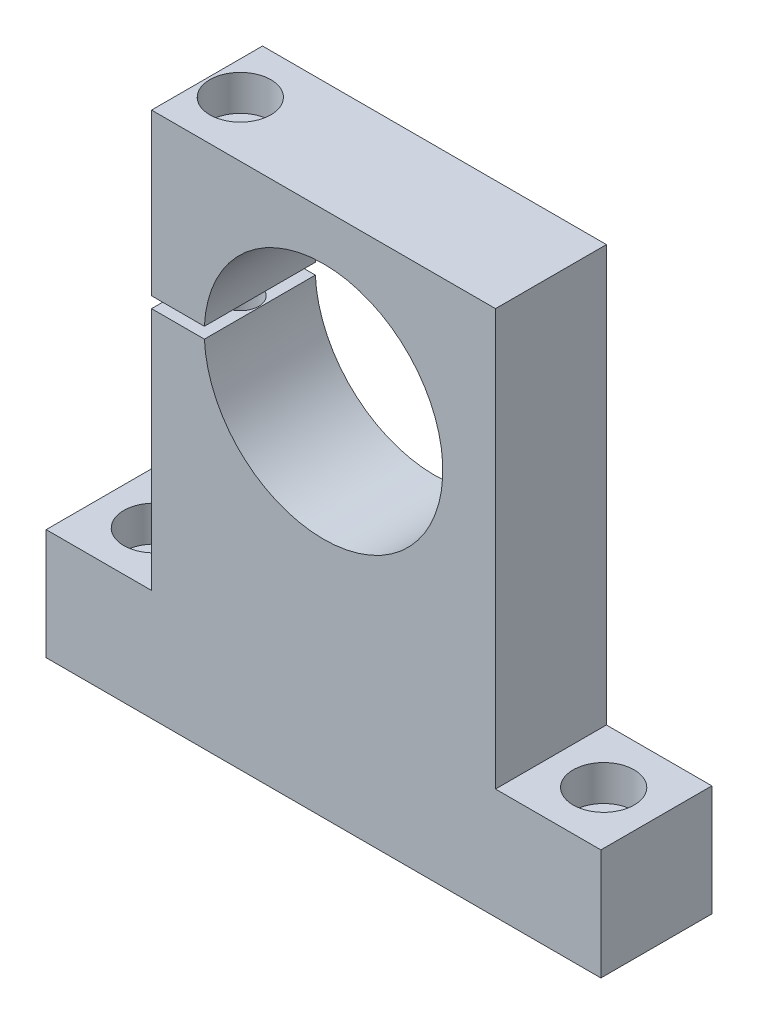
SolidWorks part; units mm, degrees
ref_plane "Piano frontale" through (0, 0, 0) normal (0, 0, 1) x (1, 0, 0)
ref_plane "Piano superiore" through (0, 0, 0) normal (0, 1, 0) x (1, 0, 0)
ref_plane "Piano destro" through (0, 0, 0) normal (1, 0, 0) x (0, 0, -1)
sketch "Schizzo1" plane through (0, 0, 0) normal (0, 0, 1) x (1, 0, 0)
  line L0 (0, 0) -> (100, 0)
  line L1 (0, 0) -> (0, 20)
  line L2 (0, 20) -> (19, 20)
  line L3 (19, 20) -> (19, 95)
  line L4 (19, 95) -> (81, 95)
  line L5 (50, 0) -> (50, 95) construction
  line L6 (100, 20) -> (81, 20)
  line L7 (100, 0) -> (100, 20)
  line L8 (81, 20) -> (81, 95)
  circle A0 centre (50, 65) radius 21.5
  dimension "D4" = 43
  dimension "D1" = 50
  dimension "D2" = 20
  dimension "D3" = 75
  dimension "D5" = 30
  dimension "D6" = 19
extrude "Estrusione-Estrusione1" add sketch "Schizzo1" along normal blind 20
sketch "Schizzo2" plane through (0, 20, 0) normal (0, 1, 0) x (1, 0, 0)
  line L0 (0, -10) -> (100, -10) construction
  line L1 (0, -20) -> (0, 0) construction
  line L2 (100, -20) -> (100, 0) construction
  line L3 (9.5, 0) -> (9.5, -20) construction
  line L4 (19, 0) -> (0, 0) construction
  line L5 (19, -20) -> (0, -20) construction
  line L6 (50, 0) -> (50, -20) construction
  line L7 (81, 0) -> (19, 0) construction
  line L8 (81, -20) -> (19, -20) construction
  point P12 (9.5, -10)
  point P19 (90.5, -10)
hole_wizard "Foro lamato per Vite M6 a testa cilindrica-1" positions "Schizzo3D2" profile "Schizzo4" counterbore size "M6" standard "ISO" end condition through all
sketch3d "Schizzo3D2"
  point P0 (9.5, 20, 10)
  point P3 (90.5, 20, 10)
sketch "Schizzo4" plane through (9.5, 20, 10) normal (1, 0, 0) x (0, 0, 1)
  line L0 (0, 0) -> (0, 20)
  line L1 (0, 20) -> (3.3, 20)
  line L3 (3.3, 20) -> (3.3, 6.4)
  line L4 (3.3, 6.4) -> (5.5, 6.4)
  line L5 (5.5, 6.4) -> (5.5, 0)
  line L7 (5.5, 0) -> (0, 0)
  line L11 (0, -6.35) -> (0, 107.95) construction
  dimension "Thru Hole Dia." = 6.6
  dimension "Thru Hole Depth" = 20
  dimension "C'Bore Dia." = 11
  dimension "C'Bore Depth" = 6.4
sketch "Schizzo5" plane through (0, 95, 0) normal (0, 1, 0) x (1, 0, 0)
  line L0 (19, -10) -> (80.6806, -10) construction
  line L1 (19, -20) -> (19, 0) construction
  line L2 (0, -10) -> (100, -10) construction
  line L3 (19, -20) -> (19, 0) construction
  point P6 (25, -10)
  dimension "D1" = 6
hole_wizard "Foro lamato per Vite M6 a testa cilindrica-2" positions "Schizzo3D3" profile "Schizzo6" counterbore size "M6" standard "ISO" end condition through all
sketch3d "Schizzo3D3"
  point P0 (25, 95, 10)
sketch "Schizzo6" plane through (25, 95, 10) normal (1, 0, 0) x (0, 0, 1)
  line L0 (0, 0) -> (0, 95)
  line L1 (0, 95) -> (3.3, 95)
  line L3 (3.3, 95) -> (3.3, 6.4)
  line L4 (3.3, 6.4) -> (5.5, 6.4)
  line L5 (5.5, 6.4) -> (5.5, 0)
  line L7 (5.5, 0) -> (0, 0)
  line L11 (0, -6.35) -> (0, 107.95) construction
  dimension "Thru Hole Dia." = 6.6
  dimension "Thru Hole Depth" = 95
  dimension "C'Bore Dia." = 11
  dimension "C'Bore Depth" = 6.4
sketch "Schizzo7" plane through (0, 0, 0) normal (0, 0, -1) x (-1, 0, 0)
  line L0 (-50, 65) -> (-5.4537, 65) construction
  line L2 (-15.9047, 64) -> (-31.4261, 64)
  line L3 (-15.9047, 64) -> (-15.9047, 66)
  line L4 (-15.9047, 66) -> (-31.4261, 66)
  line L5 (-31.4261, 64) -> (-31.4261, 66)
  line L6 (-15.9047, 64) -> (-31.4261, 66) construction
  line L7 (-15.9047, 66) -> (-31.4261, 64) construction
  point P3 (-23.6654, 65)
  dimension "D1" = 2
extrude "Taglio-Estrusione1" cut sketch "Schizzo7" against normal through all
